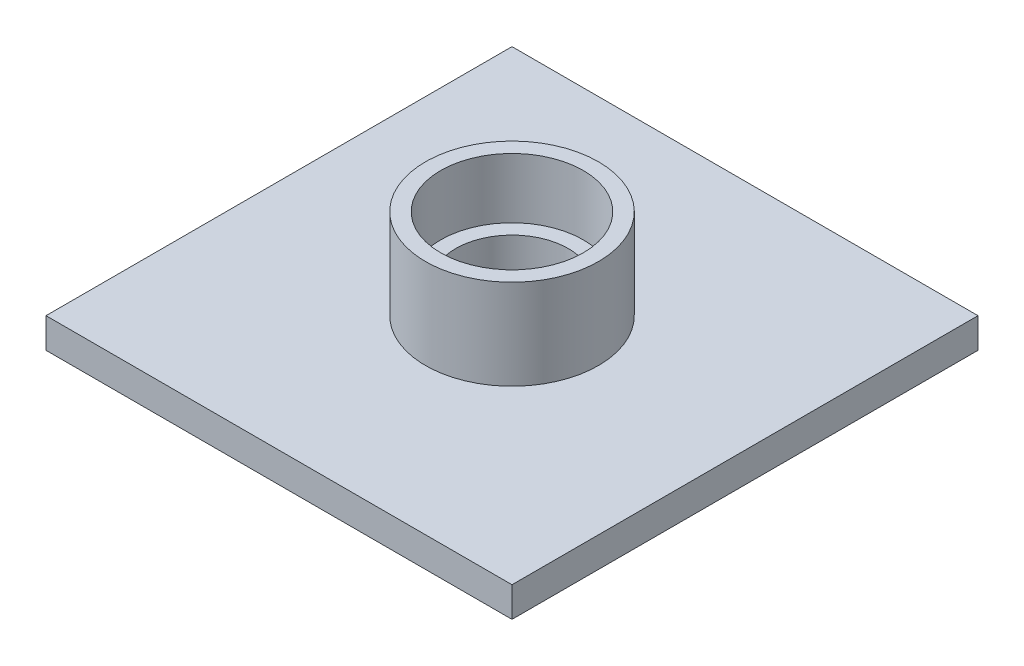
SolidWorks part; units mm, degrees
ref_plane "Front Plane" through (0, 0, 0) normal (0, 0, 1) x (1, 0, 0)
ref_plane "Top Plane" through (0, 0, 0) normal (0, 1, 0) x (1, 0, 0)
ref_plane "Right Plane" through (0, 0, 0) normal (1, 0, 0) x (0, 0, -1)
sketch "Sketch1" plane through (0, 0, 0) normal (0, 1, 0) x (1, 0, 0)
  circle A0 centre (0, 0) radius 23.8125
  circle A1 centre (0, 0) radius 30.1625
  dimension "D1" = 47.625
  dimension "D2" = 60.325
extrude "ID" add sketch "Sketch1" along normal blind 25.4
sketch "Sketch2" plane through (0, 0, 0) normal (0, -1, 0) x (1, 0, 0)
  circle A0 centre (0, 0) radius 30.1625
  circle A1 centre (0, 0) radius 36.576
  dimension "D1" = 60.325
  dimension "D2" = 73.152
extrude "OD" add sketch "Sketch2" against normal blind 50.8
sketch "Sketch4" plane through (0, 0, 0) normal (0, -1, 0) x (1, 0, 0)
  line L1 (0, 0) -> (-98.552, 0) construction
  line L2 (0, 0) -> (0, 98.552) construction
  line L3 (0, 98.552) -> (-98.552, 98.552)
  line L4 (-98.552, 0) -> (-98.552, 98.552)
  line L5 (0, 0) -> (-98.552, 0) construction
  line L6 (0, 0) -> (0, -98.552) construction
  line L7 (0, -98.552) -> (-98.552, -98.552)
  line L8 (-98.552, 0) -> (-98.552, -98.552)
  line L9 (0, 0) -> (98.552, 0) construction
  line L10 (0, 0) -> (0, -98.552) construction
  line L11 (0, -98.552) -> (98.552, -98.552)
  line L12 (98.552, 0) -> (98.552, -98.552)
  line L13 (0, 0) -> (98.552, 0) construction
  line L14 (0, 0) -> (0, 98.552) construction
  line L15 (0, 98.552) -> (98.552, 98.552)
  line L16 (98.552, 0) -> (98.552, 98.552)
  circle A0 centre (0, 0) radius 23.8125
  dimension "D1" = 98.552
  dimension "D2" = 98.552
  dimension "D3" = 98.552
extrude "Boss-Extrude3" add sketch "Sketch4" against normal blind 12.7
